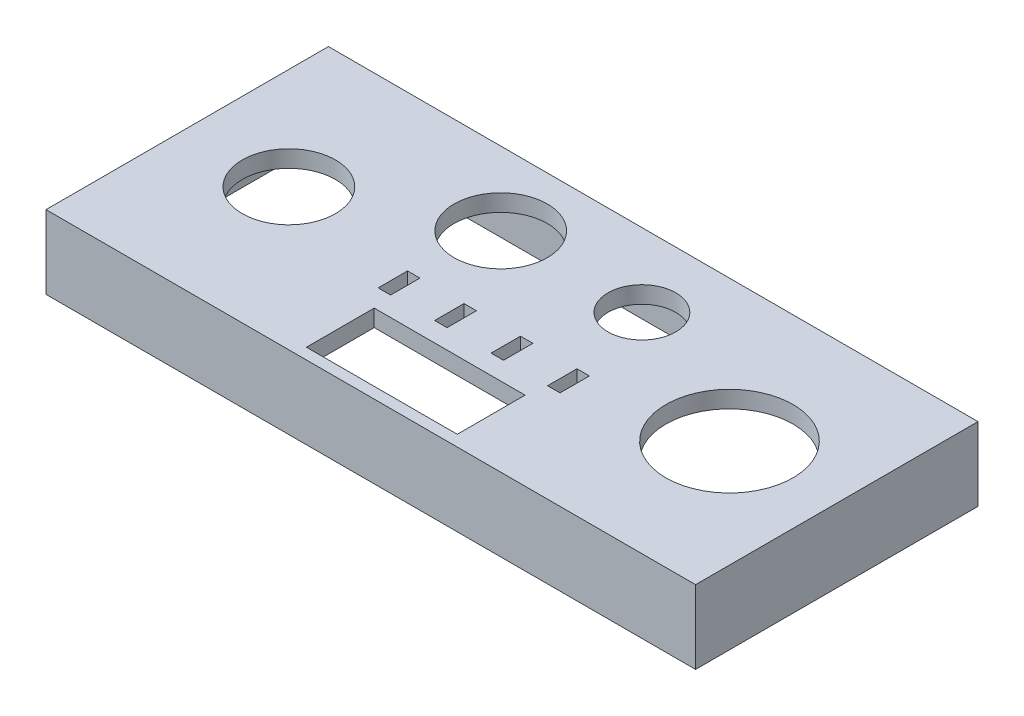
SolidWorks part; units mm, degrees
ref_plane "前视基准面" through (0, 0, 0) normal (0, 0, 1) x (1, 0, 0)
ref_plane "上视基准面" through (0, 0, 0) normal (0, 1, 0) x (1, 0, 0)
ref_plane "右视基准面" through (0, 0, 0) normal (1, 0, 0) x (0, 0, -1)
sketch "草图1" plane through (0, 0, 0) normal (0, 1, 0) x (1, 0, 0)
  line L1 (-57.5, 25) -> (57.5, 25)
  line L2 (-57.5, 25) -> (-57.5, -25)
  line L3 (-57.5, -25) -> (57.5, -25)
  line L4 (57.5, 25) -> (57.5, -25)
  line L5 (-57.5, 25) -> (57.5, -25) construction
  line L6 (-57.5, -25) -> (57.5, 25) construction
  point P0 (0, 0)
  dimension "D1" = 115
  dimension "D2" = 50
extrude "凸台-拉伸1" add sketch "草图1" along normal blind 13
sketch "草图2" plane through (0, 0, 0) normal (0, -1, 0) x (1, 0, 0)
  line L1 (-56.5, 24) -> (56.5, 24)
  line L2 (-56.5, 24) -> (-56.5, -24)
  line L3 (-56.5, -24) -> (56.5, -24)
  line L4 (56.5, 24) -> (56.5, -24)
  line L5 (-56.5, 24) -> (56.5, -24) construction
  line L6 (-56.5, -24) -> (56.5, 24) construction
  point P0 (0, 0)
  dimension "D1" = 48
  dimension "D2" = 113
extrude "切除-拉伸1" cut sketch "草图2" against normal blind 10
sketch "草图3" plane through (0, 13, 0) normal (0, 1, 0) x (1, 0, 0)
  line L0 (0, 0) -> (-57.5, 0) construction
  line L1 (-57.5, 25) -> (-57.5, -25) construction
  line L2 (0, 0) -> (57.5, 0) construction
  line L3 (57.5, -25) -> (57.5, 25) construction
  line L4 (-14, 12) -> (22.4307, 12) construction
  line L5 (0, 0) -> (0, -29.0607) construction
  line L6 (-15, -5) -> (35.6136, -5) construction
  line L7 (-13.35, -11.0399) -> (13.35, -11.0399)
  line L8 (-13.35, -11.0399) -> (-13.35, -23.0399)
  line L9 (-13.35, -23.0399) -> (13.35, -23.0399)
  line L10 (13.35, -11.0399) -> (13.35, -23.0399)
  line L11 (-13.35, -11.0399) -> (13.35, -23.0399) construction
  line L12 (-13.35, -23.0399) -> (13.35, -11.0399) construction
  line L13 (-16.1, -7.6) -> (-13.9, -7.6)
  line L14 (-16.1, -7.6) -> (-16.1, -2.4)
  line L15 (-16.1, -2.4) -> (-13.9, -2.4)
  line L16 (-13.9, -7.6) -> (-13.9, -2.4)
  line L17 (-16.1, -7.6) -> (-13.9, -2.4) construction
  line L18 (-16.1, -2.4) -> (-13.9, -7.6) construction
  line L20 (16.1, -2.4) -> (13.9, -2.4)
  line L21 (16.1, -2.4) -> (16.1, -7.6)
  line L22 (16.1, -7.6) -> (13.9, -7.6)
  line L23 (13.9, -2.4) -> (13.9, -7.6)
  line L24 (16.1, -2.4) -> (13.9, -7.6) construction
  line L25 (16.1, -7.6) -> (13.9, -2.4) construction
  line L26 (6.1, -2.4) -> (3.9, -2.4)
  line L27 (6.1, -2.4) -> (6.1, -7.6)
  line L28 (6.1, -7.6) -> (3.9, -7.6)
  line L29 (3.9, -2.4) -> (3.9, -7.6)
  line L30 (6.1, -2.4) -> (3.9, -7.6) construction
  line L31 (6.1, -7.6) -> (3.9, -2.4) construction
  line L32 (-6.1, -2.4) -> (-3.9, -2.4)
  line L33 (-6.1, -2.4) -> (-6.1, -7.6)
  line L34 (-6.1, -7.6) -> (-3.9, -7.6)
  line L35 (-3.9, -2.4) -> (-3.9, -7.6)
  line L36 (-6.1, -2.4) -> (-3.9, -7.6) construction
  line L37 (-6.1, -7.6) -> (-3.9, -2.4) construction
  line L38 (57.5, 25) -> (-57.5, 25) construction
  line L39 (0, 0) -> (0, 25.7079) construction
  circle A0 centre (-39.5, 0) radius 8.25
  circle A1 centre (38.5, 0) radius 11.25
  circle A2 centre (-14, 12) radius 8.25
  circle A3 centre (11, 12) radius 6
  point P10 (-15, -5)
  point P19 (0, -17.0399)
  point P30 (15, -5)
  point P35 (5, -5)
  point P40 (-5, -5)
  dimension "D1" = 12
  dimension "D21" = 19
  dimension "D2" = 26.7
  dimension "D3" = 2.2
  dimension "D4" = 5.2
  dimension "D5" = 2.2
  dimension "D6" = 5.2
  dimension "D7" = 2.2
  dimension "D8" = 5.2
  dimension "D9" = 2.2
  dimension "D10" = 5.2
  dimension "D11" = 15
  dimension "D12" = 15
  dimension "D13" = 5
  dimension "D14" = 5
  dimension "D15" = 13
  dimension "D16" = 11
  dimension "D17" = 14
  dimension "D18" = 5
  dimension "D22" = 18
extrude "切除-拉伸2" cut sketch "草图3" against normal blind 10
